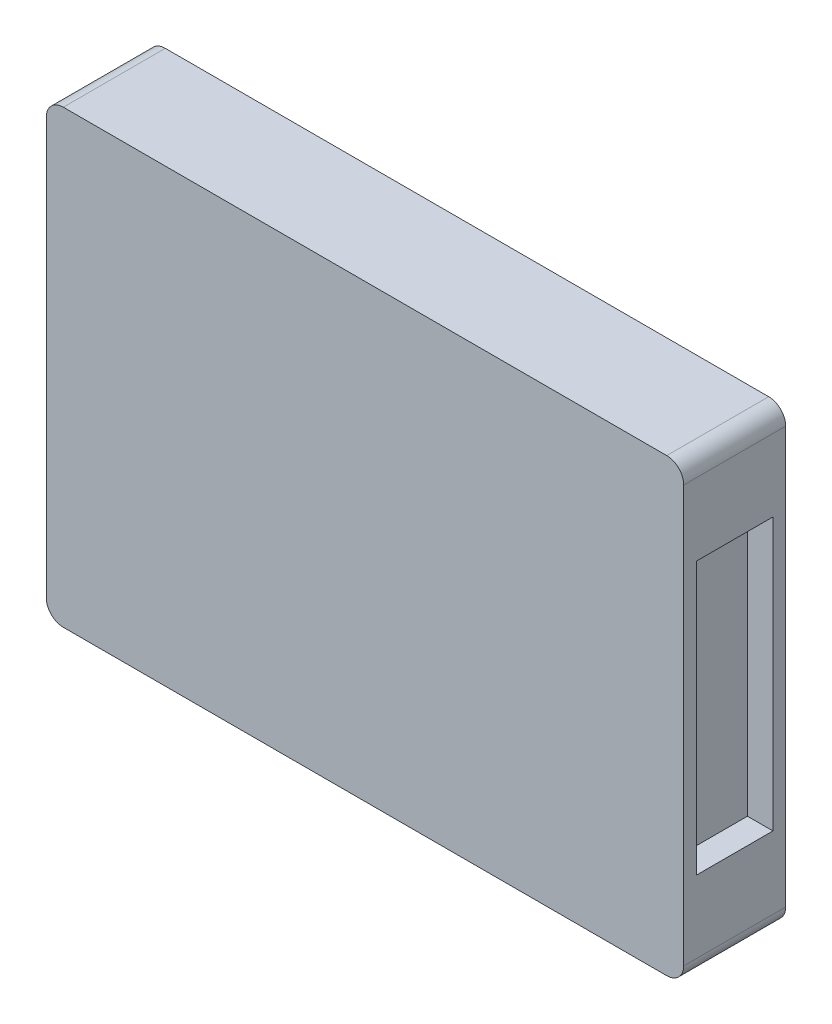
SolidWorks part; units mm, degrees
ref_plane "前视基准面" through (0, 0, 0) normal (0, 0, 1) x (1, 0, 0)
ref_plane "上视基准面" through (0, 0, 0) normal (0, 1, 0) x (1, 0, 0)
ref_plane "右视基准面" through (0, 0, 0) normal (1, 0, 0) x (0, 0, -1)
sketch "草图1" plane through (0, 0, 0) normal (0, 0, 1) x (1, 0, 0)
  line L1 (37.5, -26.5) -> (-37.5, -26.5)
  line L2 (37.5, -26.5) -> (37.5, 26.5)
  line L3 (37.5, 26.5) -> (-37.5, 26.5)
  line L4 (-37.5, -26.5) -> (-37.5, 26.5)
  line L5 (37.5, -26.5) -> (-37.5, 26.5) construction
  line L6 (37.5, 26.5) -> (-37.5, -26.5) construction
  point P0 (0, 0)
  dimension "D1" = 75
  dimension "D2" = 53
extrude "凸台-拉伸1" add sketch "草图1" along normal blind 12
fillet "圆角1" radius 2 4 edges at (37.5, 26.5, 6) (37.5, -26.5, 6) (-37.5, -26.5, 6) (-37.5, 26.5, 6)
sketch "草图2" plane through (37.5, 0, 0) normal (1, 0, 0) x (0, 0, -1)
  line L0 (0, -24.5) -> (0, 24.5) construction
  line L1 (-1.5, -16) -> (-10.5, -16)
  line L2 (-1.5, -16) -> (-1.5, 16)
  line L3 (-1.5, 16) -> (-10.5, 16)
  line L4 (-10.5, -16) -> (-10.5, 16)
  line L5 (-1.5, -16) -> (-10.5, 16) construction
  line L6 (-1.5, 16) -> (-10.5, -16) construction
  line L7 (-12, 26.5) -> (0, 26.5) construction
  point P0 (-6, 0)
  dimension "D1" = 6
  dimension "D2" = 26.5
  dimension "D3" = 9
  dimension "D4" = 32
extrude "切除-拉伸1" cut sketch "草图2" against normal blind 3
sketch "草图3" plane through (-37.5, 0, 0) normal (-1, 0, 0) x (0, 0, 1)
  line L0 (6, -4) -> (6, 4) construction
  line L1 (3.5, -4) -> (3.5, 4)
  line L2 (8.5, -4) -> (8.5, 4)
  arc A0 (3.5, -4) -> (8.5, -4) centre (6, -4) ccw
  arc A1 (8.5, 4) -> (3.5, 4) centre (6, 4) ccw
  point P2 (6, 0)
  dimension "D1" = 8
  dimension "D2" = 5
  dimension "D3" = 6
  dimension "D4" = 0
extrude "切除-拉伸2" cut sketch "草图3" against normal blind 3
